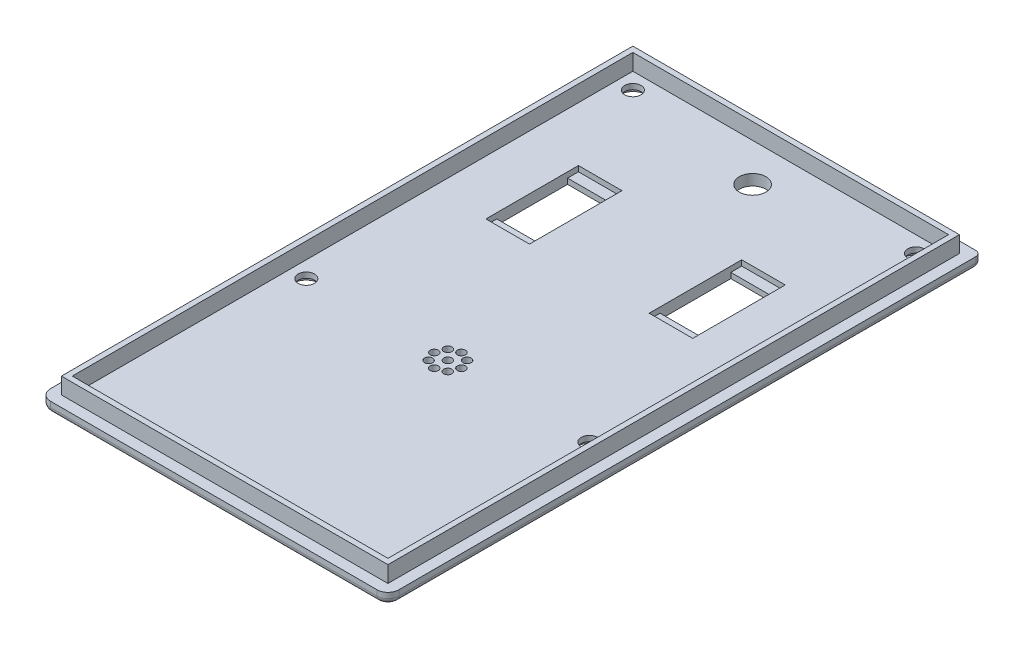
SolidWorks part; units mm, degrees
ref_plane "Front Plane" through (0, 0, 0) normal (0, 0, 1) x (1, 0, 0)
ref_plane "Top Plane" through (0, 0, 0) normal (0, 1, 0) x (1, 0, 0)
ref_plane "Right Plane" through (0, 0, 0) normal (1, 0, 0) x (0, 0, -1)
sketch "Sketch1" plane through (0, 0, 0) normal (0, 1, 0) x (1, 0, 0)
  line L1 (32, -54.5) -> (-32, -54.5)
  line L2 (32, -54.5) -> (32, 54.5)
  line L3 (32, 54.5) -> (-32, 54.5)
  line L4 (-32, -54.5) -> (-32, 54.5)
  line L5 (32, -54.5) -> (-32, 54.5) construction
  line L6 (32, 54.5) -> (-32, -54.5) construction
  point P0 (0, 0)
  dimension "D1" = 64
  dimension "D2" = 109
extrude "Boss-Extrude1" add sketch "Sketch1" along normal blind 2
sketch "Sketch2" plane through (0, 2, 0) normal (0, 1, 0) x (1, 0, 0)
  line L1 (30, -52.5) -> (-30, -52.5)
  line L2 (30, -52.5) -> (30, 52.5)
  line L3 (30, 52.5) -> (-30, 52.5)
  line L4 (-30, -52.5) -> (-30, 52.5)
  line L5 (30, -52.5) -> (-30, 52.5) construction
  line L6 (30, 52.5) -> (-30, -52.5) construction
  point P0 (0, 0)
  dimension "D1" = 105
  dimension "D2" = 60
extrude "Boss-Extrude2" add sketch "Sketch2" along normal blind 3
sketch "Sketch3" plane through (0, 5, 0) normal (0, 1, 0) x (1, 0, 0)
  line L1 (29, -51.5) -> (-29, -51.5)
  line L2 (29, -51.5) -> (29, 51.5)
  line L3 (29, 51.5) -> (-29, 51.5)
  line L4 (-29, -51.5) -> (-29, 51.5)
  line L5 (29, -51.5) -> (-29, 51.5) construction
  line L6 (29, 51.5) -> (-29, -51.5) construction
  point P0 (0, 0)
  dimension "D1" = 103
  dimension "D2" = 58
extrude "Cut-Extrude1" cut sketch "Sketch3" against normal blind 3
sketch "Sketch4" plane through (0, 2, 0) normal (0, 1, 0) x (1, 0, 0)
  line L0 (32, 54.5) -> (-32, 54.5) construction
  line L1 (-32, 54.5) -> (-32, -54.5) construction
  line L2 (0, 0) -> (0, 27.5065) construction
  circle A0 centre (-26, 48.5) radius 1.5
  circle A1 centre (-26, -11.5) radius 1.5
  circle A2 centre (26, -11.5) radius 1.5
  circle A3 centre (26, 48.5) radius 1.5
  dimension "D1" = 3
  dimension "D4" = 3
  dimension "D2" = 6
  dimension "D3" = 6
  dimension "D5" = 60
  dimension "D6" = 6
extrude "Cut-Extrude2" cut sketch "Sketch4" against normal blind 2
sketch "Sketch6" plane through (0, 0, 0) normal (0, -1, 0) x (1, 0, 0)
  circle A0 centre (26, -48.5) radius 2.5
  circle A1 centre (-26, -48.5) radius 2.5
  circle A2 centre (26, 11.5) radius 2.5
  circle A3 centre (-26, 11.5) radius 2.5
  dimension "D1" = 5
  dimension "D2" = 5
  dimension "D3" = 5
  dimension "D4" = 5
extrude "Cut-Extrude3" cut sketch "Sketch6" against normal blind 1
sketch "Sketch7" plane through (0, 2, 0) normal (0, 1, 0) x (1, 0, 0)
  line L0 (0, 52.5) -> (0, 6.7279) construction
  line L2 (32, 54.5) -> (-32, 54.5) construction
  circle A0 centre (0, 44.5) radius 2.45
  dimension "D1" = 4.9
  dimension "D2" = 10
extrude "Cut-Extrude4" cut sketch "Sketch7" against normal blind 2
sketch "Sketch8" plane through (0, 2, 0) normal (0, 1, 0) x (1, 0, 0)
  line L0 (0, 0) -> (0, -33.0483) construction
  line L1 (-19, 29.5) -> (-11, 29.5)
  line L2 (-19, 29.5) -> (-19, 16.5)
  line L3 (-19, 16.5) -> (-11, 16.5)
  line L4 (-11, 29.5) -> (-11, 16.5)
  line L5 (-19, 29.5) -> (-11, 16.5) construction
  line L6 (-19, 16.5) -> (-11, 29.5) construction
  line L7 (-32, 54.5) -> (-32, -54.5) construction
  line L8 (32, 54.5) -> (-32, 54.5) construction
  point P0 (-15, 23)
  point P10 (-15, 29.5)
  dimension "D1" = 13
  dimension "D2" = 8
  dimension "D3" = 13
  dimension "D4" = 25
extrude "Cut-Extrude5" cut sketch "Sketch8" against normal blind 2
sketch "Sketch9" plane through (0, 2, 0) normal (0, 1, 0) x (1, 0, 0)
  line L0 (0, 0) -> (0, 57.5942) construction
  line L1 (-11, 29.5) -> (-19, 29.5) construction
  line L2 (11, 29.5) -> (19, 29.5)
  line L3 (11, 29.5) -> (11, 16.5)
  line L4 (11, 16.5) -> (19, 16.5)
  line L5 (19, 29.5) -> (19, 16.5)
  line L8 (32, -54.5) -> (32, 54.5) construction
  dimension "D1" = 8
  dimension "D2" = 13
  dimension "D3" = 13
extrude "Cut-Extrude6" cut sketch "Sketch9" against normal blind 2
fillet "Fillet2" radius 1 1 edges at (32, 1, -54.5)
fillet "Fillet3" radius 1 1 edges at (-32, 1, -54.5)
fillet "Fillet4" radius 2 1 edges at (-32, 1, 54.5)
fillet "Fillet5" radius 2 1 edges at (32, 1, 54.5)
fillet "Fillet6" radius 1 8 edges at (31.7071, 0, -54.2071) (32, 0, -0.5) (31.4142, 0, 53.9142) (0, 0, 54.5) (-31.4142, 0, 53.9142) (-32, 0, -0.5) (-31.7071, 0, -54.2071) (0, 0, -54.5)
sketch "Sketch10" plane through (0, 2, 0) normal (0, 1, 0) x (1, 0, 0)
  line L0 (-11, 29.5) -> (-19, 29.5) construction
  line L1 (-19, 31.5) -> (-11, 31.5)
  line L2 (-19, 31.5) -> (-19, 14.5)
  line L3 (-19, 14.5) -> (-11, 14.5)
  line L4 (-11, 31.5) -> (-11, 14.5)
  line L5 (-19, 16.5) -> (-11, 16.5) construction
  line L7 (-11, 16.5) -> (-11, 29.5) construction
  line L8 (-19, 29.5) -> (-19, 16.5) construction
  line L9 (19, 29.5) -> (11, 29.5) construction
  line L10 (11, 31.5) -> (19, 31.5)
  line L11 (11, 31.5) -> (11, 14.5)
  line L12 (11, 14.5) -> (19, 14.5)
  line L13 (19, 31.5) -> (19, 14.5)
  line L14 (11, 16.5) -> (19, 16.5) construction
  line L15 (11, 29.5) -> (11, 16.5) construction
  line L16 (19, 16.5) -> (19, 29.5) construction
  dimension "D1" = 2
  dimension "D2" = 2
  dimension "D3" = 2
  dimension "D4" = 2
extrude "Cut-Extrude7" cut sketch "Sketch10" against normal blind 1
sketch "Sketch11" plane through (0, 2, 0) normal (0, 1, 0) x (1, 0, 0)
  line L1 (-30, -54.5) -> (30, -54.5) construction
  line L2 (0, -11.5) -> (5.9099, -11.5) construction
  line L3 (0, -11.5) -> (0, -4.8917) construction
  line L4 (0, -11.5) -> (10.1854, -1.3146) construction
  line L5 (0, -11.5) -> (-11.1968, -22.6968) construction
  line L6 (0, -11.5) -> (-10.0275, -1.4725) construction
  line L7 (0, -11.5) -> (10.7045, -22.2045) construction
  circle A0 centre (0, -11.5) radius 0.75
  circle A2 centre (0, -9) radius 0.75
  circle A3 centre (1.7678, -9.7322) radius 0.75
  circle A4 centre (2.5, -11.5) radius 0.75
  circle A5 centre (1.7678, -13.2678) radius 0.75
  circle A6 centre (0, -14) radius 0.75
  circle A7 centre (-1.7678, -9.7322) radius 0.75
  circle A8 centre (-2.5, -11.5) radius 0.75
  circle A9 centre (-1.7678, -13.2678) radius 0.75
  point P8 (0, 0)
  point P30 (0, 0)
  point P31 (0, 0)
  point P32 (0, 0)
  point P33 (0, 0)
  point P34 (0, 0)
  point P35 (-3.5108, -12.2603)
  point P36 (0, 0)
  point P37 (0, 0)
  point P38 (0, -11.6399)
  dimension "D1" = 1.5
  dimension "D2" = 43
  dimension "D3" = 1.5
  dimension "D4" = 1.5
  dimension "D5" = 1.5
  dimension "D6" = 1.5
  dimension "D7" = 1.5
  dimension "D8" = 1.5
  dimension "D9" = 1.5
  dimension "D10" = 1.5
  dimension "D11" = 2.5
  dimension "D12" = 2.5
  dimension "D13" = 2.5
  dimension "D14" = 2.5
  dimension "D15" = 2.5
  dimension "D16" = 2.5
  dimension "D17" = 2.5
  dimension "D18" = 2.5
  dimension "D19" = 45
  dimension "D20" = 45
  dimension "D21" = 45
  dimension "D22" = 45
extrude "Cut-Extrude8" cut sketch "Sketch11" against normal blind 2
